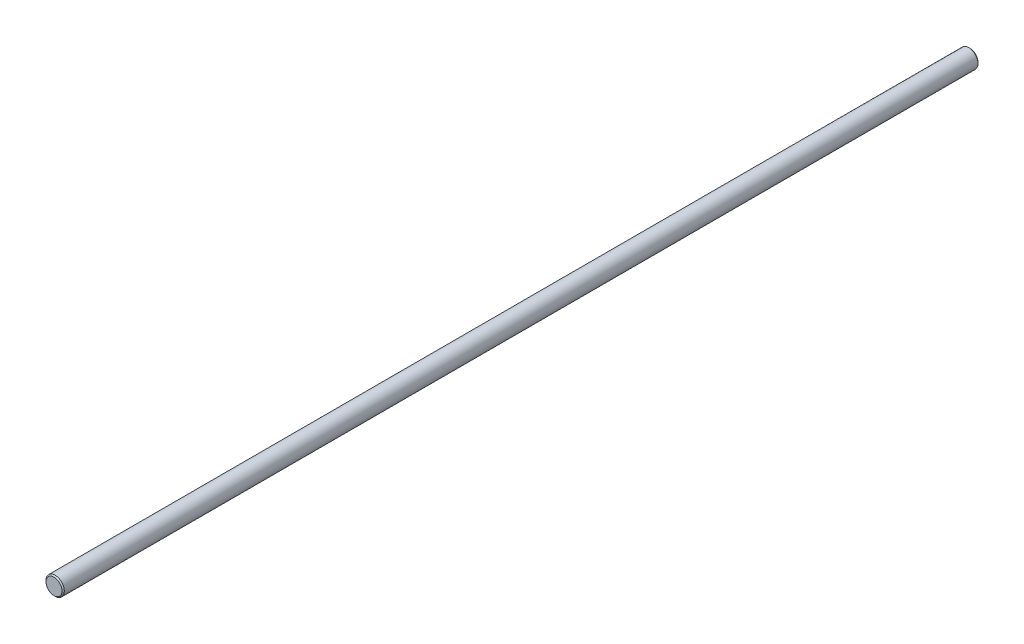
SolidWorks part; units mm, degrees
ref_plane "Front Plane" through (0, 0, 0) normal (0, 0, 1) x (1, 0, 0)
ref_plane "Top Plane" through (0, 0, 0) normal (0, 1, 0) x (1, 0, 0)
ref_plane "Right Plane" through (0, 0, 0) normal (1, 0, 0) x (0, 0, -1)
sketch "Sketch1" plane through (0, 0, 0) normal (0, 0, 1) x (1, 0, 0)
  circle A0 centre (0, 0) radius 4
  dimension "D1" = 8
extrude "Extrude1" add sketch "Sketch1" along normal blind 400
chamfer "Chamfer1" distance 0.5 angle 45 2 edges at (4, 0, 400) (4, 0, 0)
